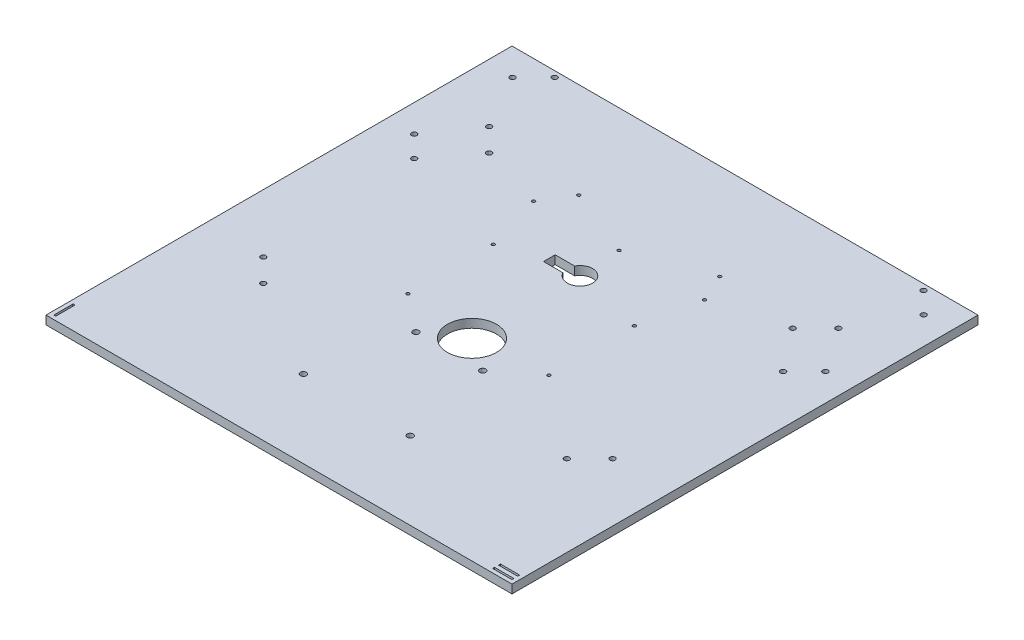
SolidWorks part; units mm, degrees
material "Acrylic (Medium-high impact)"
ref_plane "Front Plane" through (0, 0, 0) normal (0, 0, 1) x (1, 0, 0)
ref_plane "Top Plane" through (0, 0, 0) normal (0, 1, 0) x (1, 0, 0)
ref_plane "Right Plane" through (0, 0, 0) normal (1, 0, 0) x (0, 0, -1)
sketch "Sketch2" plane through (0, 0, 0) normal (0, 1, 0) x (1, 0, 0)
  line L1 (0, 0) -> (304.8, 0)
  line L2 (0, 0) -> (0, 304.8)
  line L3 (0, 304.8) -> (304.8, 304.8)
  line L4 (304.8, 0) -> (304.8, 304.8)
  dimension "D1" = 304.8
  dimension "D2" = 304.8
extrude "Boss-Extrude1" add sketch "Sketch2" along normal blind 5.588
sketch "Sketch4" plane through (0, 5.588, 0) normal (0, 1, 0) x (1, 0, 0)
  line L0 (0, 304.8) -> (0, 0) construction
  line L1 (2.54, 2.54) -> (3.81, 2.54)
  line L2 (2.54, 2.54) -> (2.54, 15.24)
  line L3 (2.54, 15.24) -> (3.81, 15.24)
  line L4 (3.81, 2.54) -> (3.81, 15.24)
  line L5 (2.54, 302.26) -> (3.81, 302.26) construction
  line L6 (2.54, 302.26) -> (2.54, 289.56) construction
  line L7 (2.54, 289.56) -> (3.81, 289.56) construction
  line L8 (3.81, 302.26) -> (3.81, 289.56) construction
  line L9 (6.35, 302.26) -> (7.62, 302.26) construction
  line L10 (6.35, 302.26) -> (6.35, 289.56) construction
  line L11 (6.35, 289.56) -> (7.62, 289.56) construction
  line L12 (7.62, 302.26) -> (7.62, 289.56) construction
  line L13 (304.8, 304.8) -> (0, 304.8) construction
  line L14 (0, 0) -> (304.8, 0) construction
  line L15 (304.8, 0) -> (304.8, 304.8) construction
  line L16 (302.26, 2.54) -> (289.56, 2.54)
  line L17 (302.26, 2.54) -> (302.26, 3.81)
  line L18 (302.26, 3.81) -> (289.56, 3.81)
  line L19 (289.56, 2.54) -> (289.56, 3.81)
  line L20 (302.26, 6.35) -> (289.56, 6.35)
  line L21 (302.26, 6.35) -> (302.26, 7.62)
  line L22 (302.26, 7.62) -> (289.56, 7.62)
  line L23 (289.56, 6.35) -> (289.56, 7.62)
  dimension "D1" = 12.7
  dimension "D2" = 1.27
  dimension "D3" = 2.54
  dimension "D4" = 2.54
  dimension "D5" = 2.54
  dimension "D6" = 2.54
  dimension "D7" = 2.54
  dimension "D8" = 2.54
  dimension "D9" = 2.54
  dimension "D10" = 2.54
extrude "Cut-Extrude1" cut sketch "Sketch4" against normal through all
sketch "Sketch5" plane through (0, 5.588, 0) normal (0, 1, 0) x (1, 0, 0)
  line L0 (0, 304.8) -> (0, 0) construction
  line L1 (34.5465, 268.1122) -> (263.4005, 268.1122)
  line L2 (34.5465, 268.1122) -> (34.5465, 281.0662)
  line L3 (34.5465, 281.0662) -> (263.4005, 281.0662)
  line L4 (263.4005, 268.1122) -> (263.4005, 281.0662)
  line L5 (304.8, 0) -> (304.8, 304.8) construction
  line L6 (304.8, 304.8) -> (0, 304.8) construction
  dimension "D1" = 34.5465
  dimension "D2" = 41.3995
  dimension "D3" = 23.7338
  dimension "D4" = 12.954
extrude "Cut-Extrude2" cut sketch "Sketch5" against normal blind 0.254
sketch "Sketch6" plane through (0, 5.588, 0) normal (0, 1, 0) x (1, 0, 0)
  circle A0 centre (152.48, 126.1263) radius 15.748 construction
  circle A1 centre (152.48, 126.1263) radius 15.748 construction
  circle A2 centre (152.48, 126.1263) radius 16.002
  circle A3 centre (31.75, 300.9591) radius 1.7 construction
  circle A4 centre (17.9387, 287.1479) radius 1.7 construction
  circle A5 centre (273.05, 300.9591) radius 1.7 construction
  circle A6 centre (286.8612, 287.1479) radius 1.7 construction
  circle A7 centre (286.8613, 222.9062) radius 1.7 construction
  circle A8 centre (273.05, 209.095) radius 1.7 construction
  circle A9 centre (31.75, 209.095) radius 1.7 construction
  circle A10 centre (17.9388, 222.9062) radius 1.7 construction
  circle A11 centre (31.75, 300.9591) radius 1.7
  circle A12 centre (17.9387, 287.1479) radius 1.7
  circle A13 centre (273.05, 300.9591) radius 1.7
  circle A14 centre (286.8612, 287.1479) radius 1.7
  circle A15 centre (286.8613, 222.9062) radius 1.7
  circle A16 centre (273.05, 209.095) radius 1.7
  circle A17 centre (31.75, 209.095) radius 1.7
  circle A18 centre (17.9388, 222.9062) radius 1.7
  circle A19 centre (38.1788, 103.933) radius 1.7 construction
  circle A20 centre (53.133, 88.9788) radius 1.7 construction
  circle A21 centre (251.667, 88.9788) radius 1.7 construction
  circle A22 centre (266.6212, 103.933) radius 1.7 construction
  circle A23 centre (266.6212, 251.667) radius 1.7 construction
  circle A24 centre (251.667, 236.7127) radius 1.7 construction
  circle A25 centre (53.133, 236.7127) radius 1.7 construction
  circle A26 centre (38.1788, 251.667) radius 1.7 construction
  circle A27 centre (38.1788, 103.933) radius 1.7
  circle A28 centre (53.133, 88.9788) radius 1.7
  circle A29 centre (251.667, 88.9788) radius 1.7
  circle A30 centre (266.6212, 103.933) radius 1.7
  circle A31 centre (266.6212, 251.667) radius 1.7
  circle A32 centre (251.667, 236.7127) radius 1.7
  circle A33 centre (53.133, 236.7127) radius 1.7
  circle A34 centre (38.1788, 251.667) radius 1.7
  circle A35 centre (117.555, 50.8216) radius 4.5 construction
  circle A36 centre (187.405, 50.8216) radius 4.5 construction
  circle A37 centre (174.3081, 111.328) radius 4.5 construction
  circle A38 centre (130.6519, 111.328) radius 4.5 construction
  circle A39 centre (117.555, 50.8216) radius 4.5 construction
  circle A40 centre (187.405, 50.8216) radius 4.5 construction
  circle A41 centre (174.3081, 111.328) radius 4.5 construction
  circle A42 centre (130.6519, 111.328) radius 4.5 construction
  circle A43 centre (130.6519, 111.328) radius 1.96
  circle A44 centre (174.3081, 111.328) radius 1.96
  circle A45 centre (187.405, 50.8216) radius 1.96
  circle A46 centre (117.555, 50.8216) radius 1.96
  dimension "D1" = 0.254
  dimension "D2" = 2.54
extrude "Cut-Extrude3" cut sketch "Sketch6" against normal through all
sketch "Sketch7" plane through (0, 5.588, 0) normal (0, 1, 0) x (1, 0, 0)
  line L0 (152.4, 304.8) -> (152.4, 0) construction
  line L1 (304.8, 304.8) -> (0, 304.8) construction
  line L2 (0, 0) -> (304.8, 0) construction
  line L4 (145.0768, 200.66) -> (132.3768, 200.66)
  line L5 (145.0768, 200.66) -> (145.0768, 193.04) construction
  line L6 (145.0768, 193.04) -> (132.3768, 193.04)
  line L7 (132.3768, 200.66) -> (132.3768, 193.04)
  circle A0 centre (152.4, 196.85) radius 8.255 construction
  arc A1 (145.0768, 200.66) -> (145.0768, 193.04) centre (152.4, 196.85) cw
  dimension "D2" = 16.51
  dimension "D1" = 107.95
  dimension "D3" = 7.62
  dimension "D4" = 12.7
extrude "Cut-Extrude4" cut sketch "Sketch7" against normal through all
sketch "Sketch8" plane through (0, 5.588, 0) normal (0, 1, 0) x (1, 0, 0)
  circle A0 centre (94.94, 223.995) radius 0.762 construction
  circle A1 centre (150.82, 223.995) radius 0.762 construction
  circle A2 centre (206.7, 223.995) radius 0.762 construction
  circle A3 centre (94.94, 223.995) radius 0.762 construction
  circle A4 centre (150.82, 223.995) radius 0.762 construction
  circle A5 centre (206.7, 223.995) radius 0.762 construction
  circle A6 centre (206.7, 223.995) radius 1.016
  circle A7 centre (150.82, 223.995) radius 1.016
  circle A8 centre (94.94, 223.995) radius 1.016
  dimension "D1" = 0.254
extrude "Cut-Extrude5" cut sketch "Sketch8" against normal through all
sketch "Sketch9" plane through (0, 5.588, 0) normal (0, 1, 0) x (1, 0, 0)
  circle A0 centre (106.3, 242.18) radius 0.762 construction
  circle A1 centre (106.3, 186.3) radius 0.762 construction
  circle A2 centre (106.3, 130.42) radius 0.762 construction
  circle A3 centre (198.5, 130.42) radius 0.762 construction
  circle A4 centre (198.5, 186.3) radius 0.762 construction
  circle A5 centre (198.5, 242.18) radius 0.762 construction
  circle A6 centre (106.3, 242.18) radius 0.762 construction
  circle A7 centre (106.3, 186.3) radius 0.762 construction
  circle A8 centre (106.3, 130.42) radius 0.762 construction
  circle A9 centre (198.5, 130.42) radius 0.762 construction
  circle A10 centre (198.5, 186.3) radius 0.762 construction
  circle A11 centre (198.5, 242.18) radius 0.762 construction
  circle A12 centre (106.3, 242.18) radius 1.016
  circle A13 centre (106.3, 186.3) radius 1.016
  circle A14 centre (106.3, 130.42) radius 1.016
  circle A15 centre (198.5, 130.42) radius 1.016
  circle A16 centre (198.5, 186.3) radius 1.016
  circle A17 centre (198.5, 242.18) radius 1.016
  dimension "D1" = 0.254
extrude "Cut-Extrude6" cut sketch "Sketch9" against normal through all
sketch "Sketch10" plane through (0, 5.588, 0) normal (0, 1, 0) x (1, 0, 0)
  line L1 (30.0638, 287.1688) -> (266.0755, 287.1688)
  line L2 (30.0638, 287.1688) -> (30.0638, 264.2232)
  line L3 (30.0638, 264.2232) -> (266.0755, 264.2232)
  line L4 (266.0755, 287.1688) -> (266.0755, 264.2232)
extrude "Boss-Extrude3" add sketch "Sketch10" against normal through all
ref_plane "Plane1" through (152.4, 0, 0) normal (-1, 0, 0) x (0, 0, 1)
ref_plane "Plane2" through (0, 0, -152.4) normal (0, 0, 1) x (1, 0, 0)
equation "\"D8@Sketch4\"=\"D6@Sketch4\""
